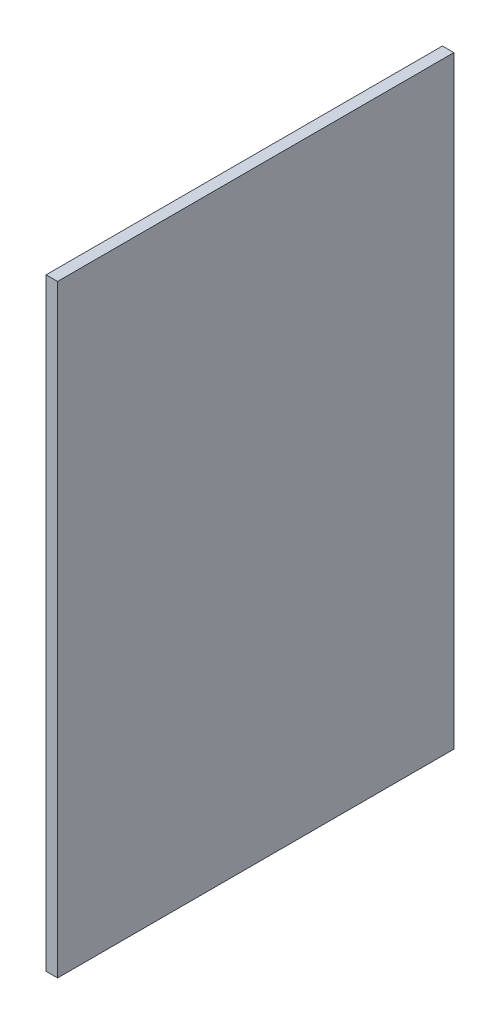
SolidWorks part; units mm, degrees
ref_plane "Front Plane" through (0, 0, 0) normal (0, 0, 1) x (1, 0, 0)
ref_plane "Top Plane" through (0, 0, 0) normal (0, 1, 0) x (1, 0, 0)
ref_plane "Right Plane" through (0, 0, 0) normal (1, 0, 0) x (0, 0, -1)
sketch "Sketch1" plane through (0, 0, 0) normal (1, 0, 0) x (0, 0, -1)
  line L1 (0, 0) -> (103.6107, 0)
  line L2 (0, 0) -> (0, 157.7195)
  line L3 (0, 157.7195) -> (103.6107, 157.7195)
  line L4 (103.6107, 0) -> (103.6107, 157.7195)
extrude "Boss-Extrude1" add sketch "Sketch1" along normal blind 3
